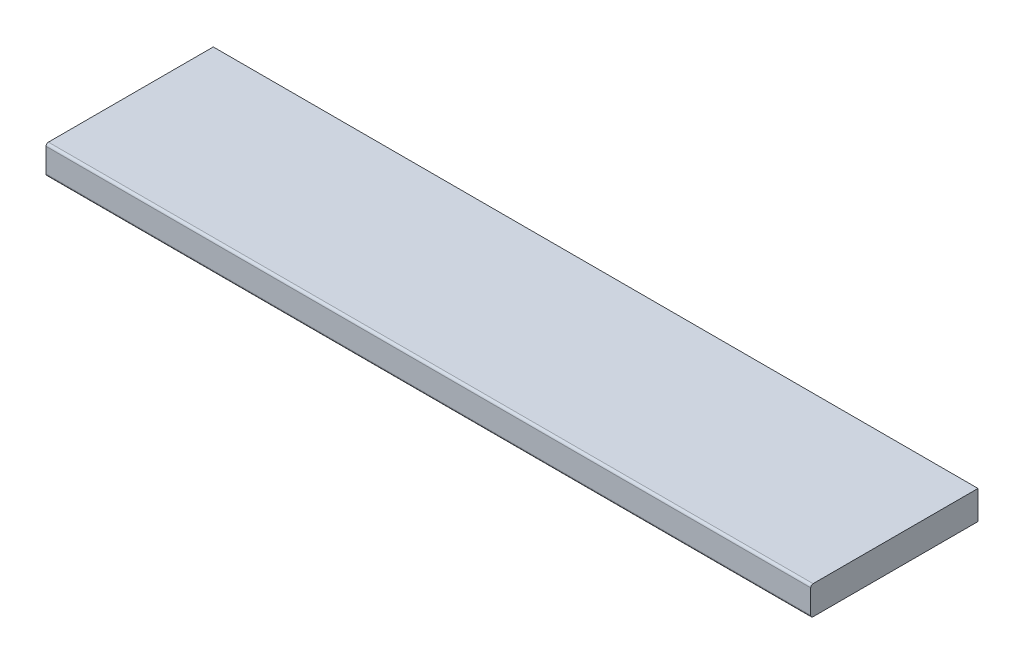
SolidWorks part; units mm, degrees
material "Сосна"
ref_plane "Спереди" through (0, 0, 0) normal (0, 0, 1) x (1, 0, 0)
ref_plane "Сверху" through (0, 0, 0) normal (0, 1, 0) x (1, 0, 0)
ref_plane "Справа" through (0, 0, 0) normal (1, 0, 0) x (0, 0, -1)
sketch "Эскиз1" plane through (0, 0, 0) normal (0, 0, 1) x (1, 0, 0)
  line L1 (-198.9474, 28.7368) -> (1401.0526, 28.7368)
  line L2 (-198.9474, 28.7368) -> (-198.9474, -31.2632)
  line L3 (-198.9474, -31.2632) -> (1401.0526, -31.2632)
  line L4 (1401.0526, 28.7368) -> (1401.0526, -31.2632)
  dimension "D1" = 60
  dimension "D2" = 1600
extrude "Подоконник малого окна" add sketch "Эскиз1" along normal blind 350
fillet "Скругление1" radius 5 2 edges at (601.0526, -31.2632, 350) (601.0526, 28.7368, 350)
